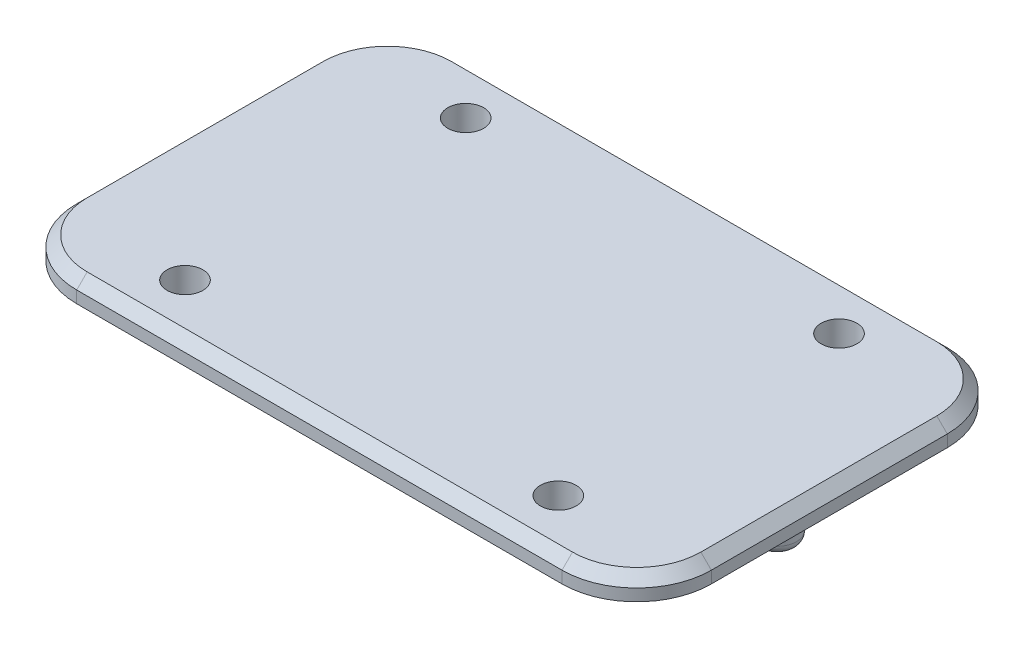
SolidWorks part; units mm, degrees
ref_plane "Front Plane" through (0, 0, 0) normal (0, 0, 1) x (1, 0, 0)
ref_plane "Top Plane" through (0, 0, 0) normal (0, 1, 0) x (1, 0, 0)
ref_plane "Right Plane" through (0, 0, 0) normal (1, 0, 0) x (0, 0, -1)
sketch "Sketch1" plane through (0, 0, 0) normal (0, 1, 0) x (1, 0, 0)
  line L0 (12.5, 10.7) -> (-12.5, 10.7)
  line L1 (-12.5, 8.1) -> (12.5, 8.1)
  line L2 (12.5, 10.9) -> (-12.5, 10.9)
  line L3 (-12.5, 7.9) -> (12.5, 7.9)
  line L4 (12.5, 10.9) -> (-12.5, 10.9) construction
  line L5 (-12.5, 7.9) -> (12.5, 7.9) construction
  line L6 (-12.5, -10.9) -> (12.5, -10.9)
  line L7 (12.5, -7.9) -> (-12.5, -7.9)
  line L8 (-12.5, -10.9) -> (12.5, -10.9) construction
  line L9 (12.5, -7.9) -> (-12.5, -7.9) construction
  line L10 (17.75, 1.5) -> (-17.75, 1.5)
  line L11 (-17.75, -1.5) -> (17.75, -1.5)
  line L12 (17.75, 1.5) -> (-17.75, 1.5) construction
  line L13 (-17.75, -1.5) -> (17.75, -1.5) construction
  line L14 (17.75, 1.3) -> (-17.75, 1.3)
  line L15 (-17.75, -1.3) -> (17.75, -1.3)
  line L16 (-12.5, -10.7) -> (12.5, -10.7)
  line L17 (12.5, -8.1) -> (-12.5, -8.1)
  line L18 (17.75, 0) -> (-17.75, 0) construction
  line L20 (21.25, 12.9) -> (-21.25, 12.9)
  line L21 (21.25, 12.9) -> (21.25, -12.9)
  line L22 (21.25, -12.9) -> (-21.25, -12.9)
  line L23 (-21.25, 12.9) -> (-21.25, -12.9)
  line L24 (21.25, 12.9) -> (-21.25, -12.9) construction
  line L25 (21.25, -12.9) -> (-21.25, 12.9) construction
  arc A0 (-12.5, 10.7) -> (-12.5, 8.1) centre (-12.5, 9.4) ccw
  arc A1 (12.5, 8.1) -> (12.5, 10.7) centre (12.5, 9.4) ccw
  arc A2 (-12.5, 10.9) -> (-12.5, 7.9) centre (-12.5, 9.4) ccw
  arc A3 (12.5, 7.9) -> (12.5, 10.9) centre (12.5, 9.4) ccw
  arc A4 (-12.5, 10.9) -> (-12.5, 7.9) centre (-12.5, 9.4) ccw construction
  arc A5 (12.5, 7.9) -> (12.5, 10.9) centre (12.5, 9.4) ccw construction
  arc A6 (12.5, -10.9) -> (12.5, -7.9) centre (12.5, -9.4) ccw
  arc A7 (-12.5, -7.9) -> (-12.5, -10.9) centre (-12.5, -9.4) ccw
  arc A8 (12.5, -10.9) -> (12.5, -7.9) centre (12.5, -9.4) ccw construction
  arc A9 (-12.5, -7.9) -> (-12.5, -10.9) centre (-12.5, -9.4) ccw construction
  arc A10 (17.75, -1.5) -> (17.75, 1.5) centre (17.75, 0) ccw
  arc A11 (-17.75, 1.5) -> (-17.75, -1.5) centre (-17.75, 0) ccw
  arc A12 (17.75, -1.5) -> (17.75, 1.5) centre (17.75, 0) ccw construction
  arc A13 (-17.75, 1.5) -> (-17.75, -1.5) centre (-17.75, 0) ccw construction
  arc A14 (17.75, -1.3) -> (17.75, 1.3) centre (17.75, 0) ccw
  arc A15 (-17.75, 1.3) -> (-17.75, -1.3) centre (-17.75, 0) ccw
  arc A16 (12.5, -10.7) -> (12.5, -8.1) centre (12.5, -9.4) ccw
  arc A17 (-12.5, -8.1) -> (-12.5, -10.7) centre (-12.5, -9.4) ccw
  point P36 (0, 0)
  point P37 (0, 0)
  point P43 (-19.25, 0)
  dimension "D5" = 2
  dimension "D6" = 2
  dimension "D1" = 0
  dimension "D2" = 0
  dimension "D3" = 0
  dimension "D4" = 0.2
sketch "Sketch2" plane through (0, 0, 0) normal (0, 1, 0) x (1, 0, 0)
  line L0 (21.25, 12.9) -> (21.25, -12.9) construction
  line L1 (21.25, 12.9) -> (-21.25, 12.9) construction
  line L2 (-21.25, 12.9) -> (-21.25, -12.9) construction
  line L3 (21.25, -12.9) -> (-21.25, -12.9) construction
  line L4 (21.25, 12.9) -> (21.25, -12.9)
  line L5 (21.25, 12.9) -> (-21.25, 12.9)
  line L6 (-21.25, 12.9) -> (-21.25, -12.9)
  line L7 (21.25, -12.9) -> (-21.25, -12.9)
extrude "Boss-Extrude1" add sketch "Sketch2" along normal blind 1.5
fillet "Fillet1" radius 5 4 edges at (21.25, 0.75, 12.9) (21.25, 0.75, -12.9) (-21.25, 0.75, -12.9) (-21.25, 0.75, 12.9)
chamfer "Chamfer1" distance 0.7 angle 45 8 edges at (21.25, 1.5, 0) (19.7855, 1.5, -11.4355) (19.7855, 1.5, 11.4355) (0, 1.5, -12.9) (0, 1.5, 12.9) (-19.7855, 1.5, -11.4355) (-19.7855, 1.5, 11.4355) (-21.25, 1.5, 0)
sketch "Sketch3" plane through (0, 0, 0) normal (0, 1, 0) x (1, 0, 0)
  line L2 (17.75, 1.3) -> (-17.75, 1.3)
  line L3 (-17.75, -1.3) -> (17.75, -1.3)
  line L4 (17.75, 1.3) -> (-17.75, 1.3)
  line L5 (-17.75, -1.3) -> (17.75, -1.3)
  line L6 (12.5, 10.7) -> (-12.5, 10.7)
  line L7 (-12.5, 8.1) -> (12.5, 8.1)
  line L8 (12.5, 10.7) -> (-12.5, 10.7)
  line L9 (-12.5, 8.1) -> (12.5, 8.1)
  line L10 (12.5, -8.1) -> (-12.5, -8.1)
  line L11 (-12.5, -10.7) -> (12.5, -10.7)
  line L12 (21.25, 12.9) -> (-21.25, 12.9)
  line L13 (-21.25, 12.9) -> (-21.25, -12.9)
  line L14 (-21.25, -12.9) -> (21.25, -12.9)
  line L15 (21.25, -12.9) -> (21.25, 12.9)
  line L16 (21.25, 12.9) -> (-21.25, 12.9) construction
  line L17 (-21.25, 12.9) -> (-21.25, -12.9) construction
  line L18 (-21.25, -12.9) -> (21.25, -12.9) construction
  line L19 (21.25, -12.9) -> (21.25, 12.9) construction
  line L20 (12.5, -8.1) -> (-12.5, -8.1)
  line L21 (-12.5, -10.7) -> (12.5, -10.7)
  arc A2 (-17.75, 1.3) -> (-17.75, -1.3) centre (-17.75, 0) ccw
  arc A3 (17.75, -1.3) -> (17.75, 1.3) centre (17.75, 0) ccw
  arc A4 (-17.75, 1.3) -> (-17.75, -1.3) centre (-17.75, 0) ccw
  arc A5 (17.75, -1.3) -> (17.75, 1.3) centre (17.75, 0) ccw
  arc A6 (12.5, 8.1) -> (12.5, 10.7) centre (12.5, 9.4) ccw
  arc A7 (-12.5, 10.7) -> (-12.5, 8.1) centre (-12.5, 9.4) ccw
  arc A8 (12.5, 8.1) -> (12.5, 10.7) centre (12.5, 9.4) ccw
  arc A9 (-12.5, 10.7) -> (-12.5, 8.1) centre (-12.5, 9.4) ccw
  arc A10 (-12.5, -8.1) -> (-12.5, -10.7) centre (-12.5, -9.4) ccw
  arc A11 (12.5, -10.7) -> (12.5, -8.1) centre (12.5, -9.4) ccw
  arc A12 (-12.5, -8.1) -> (-12.5, -10.7) centre (-12.5, -9.4) ccw
  arc A13 (12.5, -10.7) -> (12.5, -8.1) centre (12.5, -9.4) ccw
  dimension "D1" = 0
  dimension "D2" = 0
  dimension "D3" = 0
  dimension "D4" = 0
extrude "Boss-Extrude2" add sketch "Sketch3" against normal up to surface (1.5 mm away)
ref_plane "Plane1" through (0, -3.5, 0) normal (0, 1, 0) x (1, 0, 0)
sketch "Sketch4" plane through (0, -1.5, 0) normal (0, -1, 0) x (1, 0, 0)
  line L2 (17.75, 1.3) -> (-17.75, 1.3)
  line L3 (-17.75, -1.3) -> (17.75, -1.3)
  line L4 (17.75, 1.3) -> (-17.75, 1.3)
  line L5 (-17.75, -1.3) -> (17.75, -1.3)
  arc A2 (17.75, -1.3) -> (17.75, 1.3) centre (17.75, 0) ccw
  arc A3 (-17.75, 1.3) -> (-17.75, -1.3) centre (-17.75, 0) ccw
  arc A4 (17.75, -1.3) -> (17.75, 1.3) centre (17.75, 0) ccw
  arc A5 (-17.75, 1.3) -> (-17.75, -1.3) centre (-17.75, 0) ccw
  dimension "D1" = 0
extrude "Boss-Extrude3" add sketch "Sketch4" along normal offset from surface (1.7 mm away) 0.3 up to plane "Plane1"
fillet "Fillet2" radius 0.6 4 edges at (-19.05, -3.2, 0) (0, -3.2, -1.3) (19.05, -3.2, 0) (0, -3.2, 1.3)
sketch "Sketch5" plane through (0, -1.5, 0) normal (0, -1, 0) x (1, 0, 0)
  line L2 (-17.75, -1.5) -> (17.75, -1.5)
  line L3 (17.75, 1.5) -> (-17.75, 1.5)
  line L4 (-17.75, -1.5) -> (17.75, -1.5) construction
  line L5 (17.75, 1.5) -> (-17.75, 1.5) construction
  circle A0 centre (-12.5, 9.4) radius 1.2
  circle A1 centre (12.5, -9.4) radius 1.5
  circle A2 centre (12.5, -9.4) radius 1.5 construction
  circle A3 centre (12.5, 9.4) radius 1.5
  circle A4 centre (12.5, 9.4) radius 1.5 construction
  circle A5 centre (-12.5, 9.4) radius 1.5
  circle A6 centre (-12.5, 9.4) radius 1.5 construction
  circle A7 centre (-12.5, -9.4) radius 1.5
  circle A8 centre (-12.5, -9.4) radius 1.5 construction
  circle A9 centre (12.5, 9.4) radius 1.2
  arc A10 (17.75, -1.5) -> (17.75, 1.5) centre (17.75, 0) ccw
  arc A11 (-17.75, 1.5) -> (-17.75, -1.5) centre (-17.75, 0) ccw
  arc A12 (17.75, -1.5) -> (17.75, 1.5) centre (17.75, 0) ccw construction
  arc A13 (-17.75, 1.5) -> (-17.75, -1.5) centre (-17.75, 0) ccw construction
  circle A14 centre (12.5, -9.4) radius 1.2
  circle A15 centre (-12.5, -9.4) radius 1.2
  dimension "D6" = 2.4
  dimension "D1" = 0
  dimension "D2" = 0
  dimension "D3" = 0
  dimension "D4" = 0
  dimension "D5" = 0
extrude "Cut-Extrude1" cut sketch "Sketch5" against normal through all
